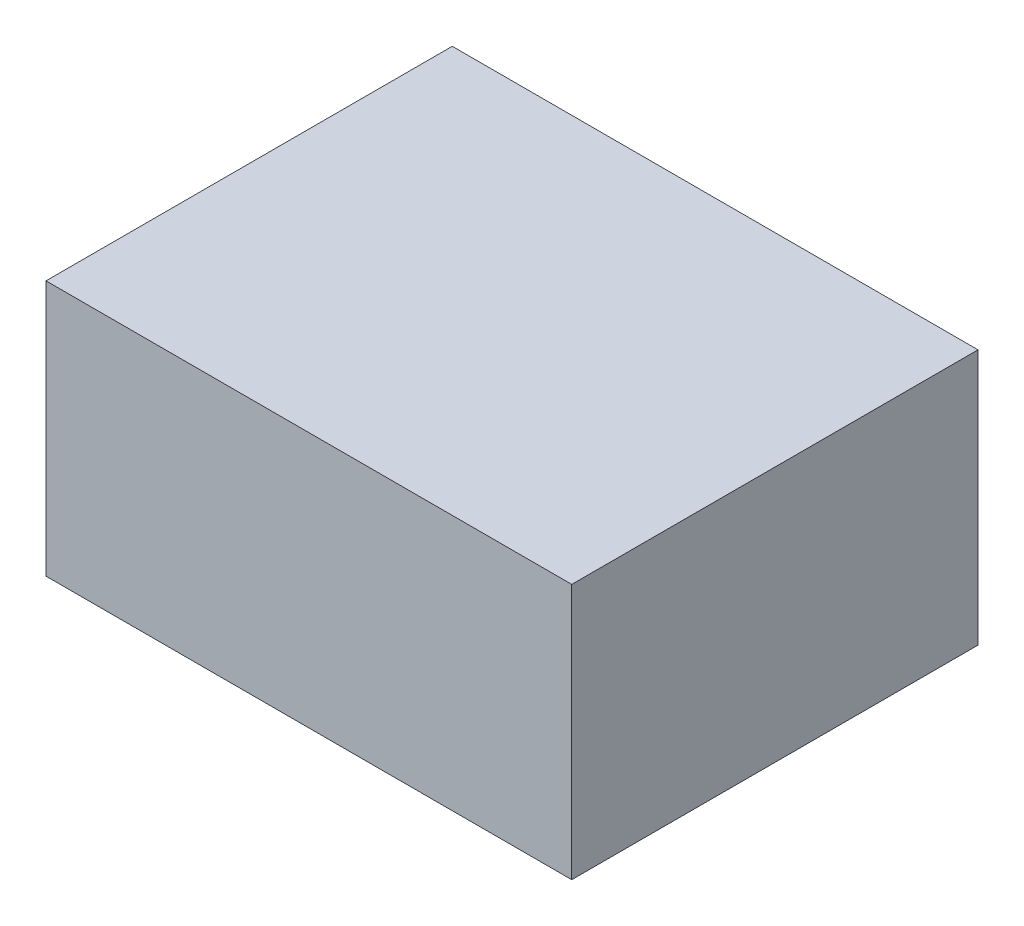
SolidWorks part; units mm, degrees
ref_plane "Front Plane" through (0, 0, 0) normal (0, 0, 1) x (1, 0, 0)
ref_plane "Top Plane" through (0, 0, 0) normal (0, 1, 0) x (1, 0, 0)
ref_plane "Right Plane" through (0, 0, 0) normal (1, 0, 0) x (0, 0, -1)
sketch "Sketch1" plane through (0, 0, 0) normal (0, 1, 0) x (1, 0, 0)
  line L1 (0, 0) -> (31.3263, 0)
  line L2 (0, 0) -> (0, -24.2067)
  line L3 (0, -24.2067) -> (31.3263, -24.2067)
  line L4 (31.3263, 0) -> (31.3263, -24.2067)
extrude "Boss-Extrude1" add sketch "Sketch1" along normal blind 15.24
